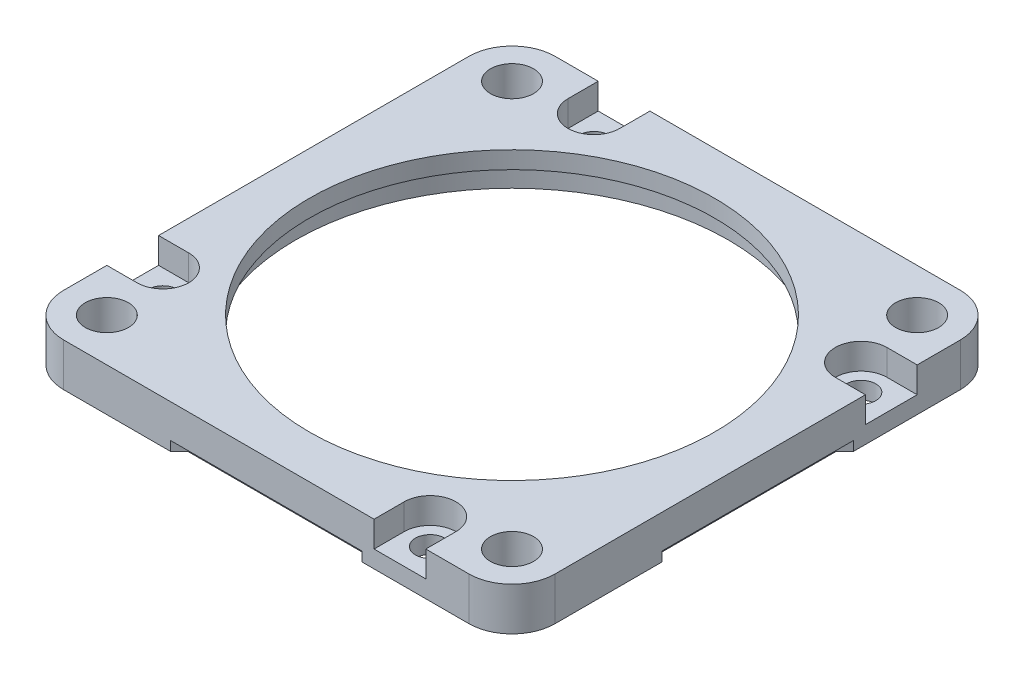
SolidWorks part; units mm, degrees
ref_plane "前视基准面" through (0, 0, 0) normal (0, 0, 1) x (1, 0, 0)
ref_plane "上视基准面" through (0, 0, 0) normal (0, 1, 0) x (1, 0, 0)
ref_plane "右视基准面" through (0, 0, 0) normal (1, 0, 0) x (0, 0, -1)
sketch "草图1" plane through (0, 0, 0) normal (0, 1, 0) x (1, 0, 0)
  line L1 (-28.5, -28.5) -> (28.5, -28.5)
  line L2 (-28.5, -28.5) -> (-28.5, 28.5)
  line L3 (-28.5, 28.5) -> (28.5, 28.5)
  line L4 (28.5, -28.5) -> (28.5, 28.5)
  line L5 (-28.5, -28.5) -> (28.5, 28.5) construction
  line L6 (-28.5, 28.5) -> (28.5, -28.5) construction
  point P0 (0, 0)
  dimension "D1" = 57
extrude "凸台-拉伸1" add sketch "草图1" along normal blind 5
sketch "草图2" plane through (0, 5, 0) normal (0, 1, 0) x (1, 0, 0)
  circle A0 centre (0, 0) radius 23.5
  dimension "D1" = 47
extrude "切除-拉伸1" cut sketch "草图2" against normal blind 2
sketch "草图3" plane through (0, 3, 0) normal (0, 1, 0) x (1, 0, 0)
  circle A0 centre (0, 0) radius 25.1
  dimension "D1" = 50.2
extrude "切除-拉伸2" cut sketch "草图3" against normal blind 3
sketch "草图4" plane through (0, 5, 0) normal (0, 1, 0) x (1, 0, 0)
  line L0 (28.5, 28.5) -> (-28.5, 28.5) construction
  line L1 (-23.5, 23.5) -> (0, 0) construction
  line L2 (0, -0.4827) -> (0, -50000.4827) construction
  circle A0 centre (-23.5, 23.5) radius 2.5
  circle A1 centre (-15.5, 25) radius 1.7
  dimension "D1" = 3.4
  dimension "D3" = 5
  dimension "D4" = 8
  dimension "D6" = 47
  dimension "D2" = 3.5
  dimension "D5" = 45
extrude "切除-拉伸3" cut sketch "草图4" against normal through all
sketch "草图5" plane through (0, 5, 0) normal (0, 1, 0) x (1, 0, 0)
  line L0 (-15.5, 25) -> (-15.5, 30.7809) construction
  line L1 (-18.5, 25) -> (-18.5, 30.7809)
  line L2 (-12.5, 25) -> (-12.5, 30.7809)
  arc A0 (-18.5, 25) -> (-12.5, 25) centre (-15.5, 25) ccw
  arc A1 (-12.5, 30.7809) -> (-18.5, 30.7809) centre (-15.5, 30.7809) ccw
  point P3 (-15.5, 27.8905)
  dimension "D1" = 6
extrude "切除-拉伸4" cut sketch "草图5" against normal blind 3
sketch "草图6" plane through (0, 0, 0) normal (0, -1, 0) x (1, 0, 0)
  line L0 (-28.5, 11.1) -> (-28.5, -11.1)
  line L1 (-28.5, -28.5) -> (-28.5, 28.5) construction
  line L2 (-28.5, -11.1) -> (-27.5, -10.1)
  line L3 (-27.5, -10.1) -> (-27.5, 10.1)
  line L4 (-27.5, 10.1) -> (-28.5, 11.1)
  line L5 (-27.5, 0) -> (0, 0) construction
  dimension "D1" = 135
  dimension "D2" = 135
  dimension "D3" = 1
  dimension "D4" = 22.2
extrude "切除-拉伸5" cut sketch "草图6" against normal blind 1.1
pattern_circular "阵列(圆周)1" count 4 over 360 about axis through (0, 0, 0) along (0, 1, 0) of "切除-拉伸3", "切除-拉伸4", "切除-拉伸5"
fillet "圆角1" radius 5 4 edges at (-28.5, 2.5, 28.5) (-28.5, 2.5, -28.5) (28.5, 2.5, -28.5) (28.5, 2.5, 28.5)
